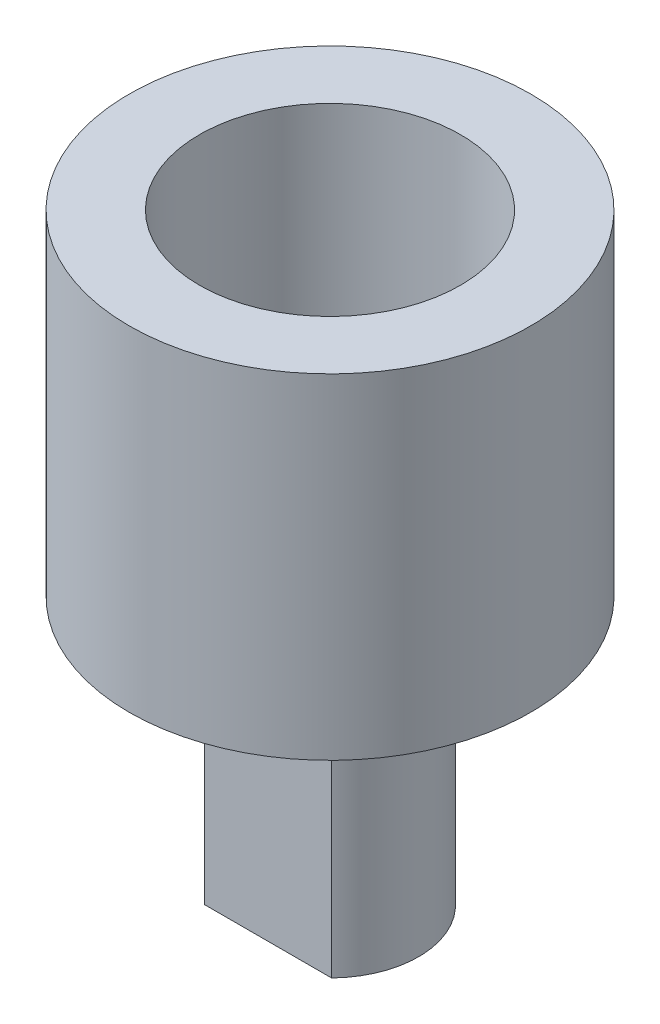
SolidWorks part; units mm, degrees
ref_plane "Front Plane" through (0, 0, 0) normal (0, 0, 1) x (1, 0, 0)
ref_plane "Top Plane" through (0, 0, 0) normal (0, 1, 0) x (1, 0, 0)
ref_plane "Right Plane" through (0, 0, 0) normal (1, 0, 0) x (0, 0, -1)
sketch "Sketch1" plane through (0, 0, 0) normal (0, 1, 0) x (1, 0, 0)
  circle A2 centre (0, 0) radius 6
  dimension "D1" = 12
extrude "Boss-Extrude1" add sketch "Sketch1" along normal blind 2
sketch "Sketch2" plane through (0, 2, 0) normal (0, 1, 0) x (1, 0, 0)
  circle A0 centre (0, 0) radius 6
  circle A1 centre (0, 0) radius 3.9
  dimension "D1" = 7.8
  dimension "D2" = 12
extrude "Boss-Extrude2" add sketch "Sketch2" along normal blind 8
sketch "Sketch3" plane through (0, 0, 0) normal (0, -1, 0) x (1, 0, 0)
  line L0 (-1.8974, 1.85) -> (1.8974, 1.85)
  line L1 (-1.9449, -1.8) -> (1.9449, -1.8)
  arc A0 (-1.8974, 1.85) -> (-1.9449, -1.8) centre (0, 0) ccw
  arc A1 (1.9449, -1.8) -> (1.8974, 1.85) centre (0, 0) ccw
  point P6 (0, 1.85)
  point P9 (3.0222, -1.6794)
  point P10 (0, -1.8)
  dimension "D1" = 5.3
  dimension "D2" = 3.65
  dimension "D3" = 1.8
extrude "Boss-Extrude3" add sketch "Sketch3" along normal blind 8
